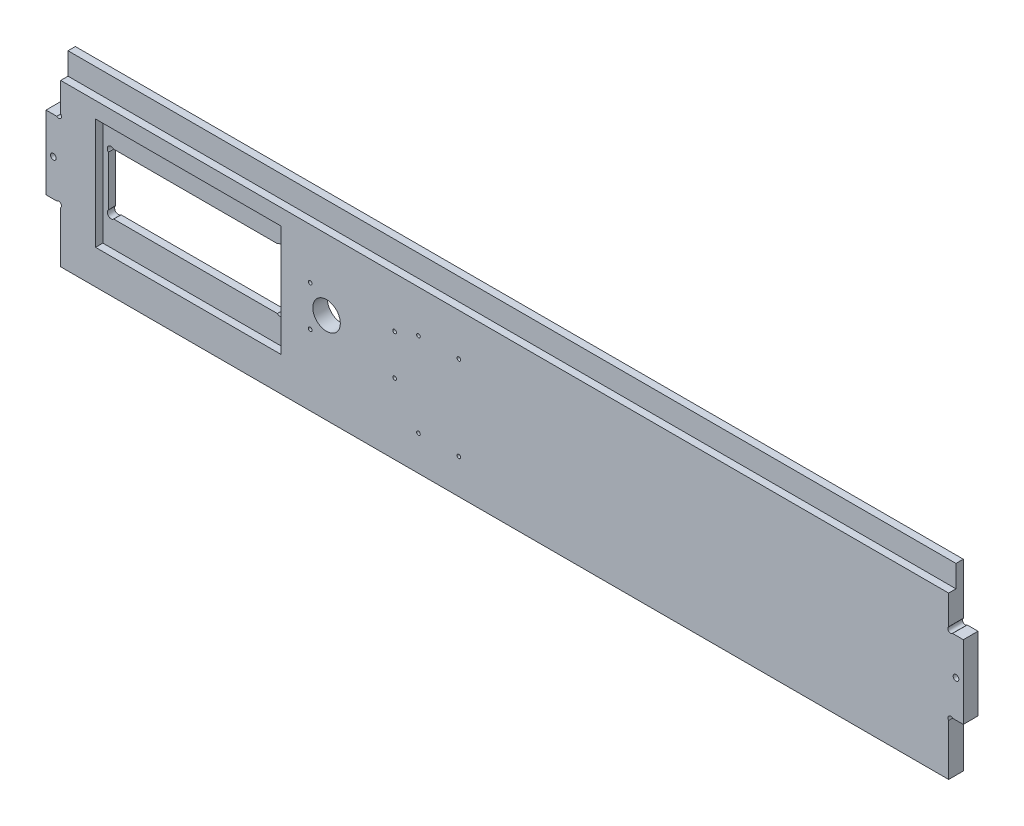
SolidWorks part; units mm, degrees
ref_plane "Plan de face" through (0, 0, 0) normal (0, 0, 1) x (1, 0, 0)
ref_plane "Plan de dessus" through (0, 0, 0) normal (0, 1, 0) x (1, 0, 0)
ref_plane "Plan de droite" through (0, 0, 0) normal (1, 0, 0) x (0, 0, -1)
sketch "Esquisse1" plane through (0, 0, 0) normal (0, 0, 1) x (1, 0, 0)
  line L0 (-399.3886, 52.3509) -> (-399.3886, 24.4722)
  line L1 (-399.3886, 52.3509) -> (84.6114, 52.3509)
  line L2 (-407.3886, 22.3509) -> (-407.3886, -17.6491)
  line L3 (-399.3886, -47.6491) -> (84.6114, -47.6491)
  line L4 (-407.3886, 2.3509) -> (92.6114, 2.3509) construction
  line L5 (-399.3886, -47.6491) -> (-399.3886, -19.7705)
  line L6 (-401.5099, -17.6491) -> (-407.3886, -17.6491)
  line L7 (-401.5099, 22.3509) -> (-407.3886, 22.3509)
  line L8 (-157.3886, 66.6557) -> (-157.3886, -74.1581) construction
  line L9 (84.6114, -47.6491) -> (84.6114, -19.7705)
  line L10 (86.7328, -17.6491) -> (92.6114, -17.6491)
  line L11 (92.6114, 22.3509) -> (92.6114, -17.6491)
  line L12 (86.7328, 22.3509) -> (92.6114, 22.3509)
  line L13 (84.6114, 52.3509) -> (84.6114, 24.4722)
  line L14 (-399.3886, 52.3509) -> (-407.3886, 52.3509) construction
  line L15 (-403.3886, 52.3509) -> (-403.3886, 2.3509) construction
  arc A0 (-401.5099, 22.3509) -> (-399.3886, 24.4722) centre (-400.4492, 23.4115) ccw
  arc A1 (-399.3886, -19.7705) -> (-401.5099, -17.6491) centre (-400.4492, -18.7098) ccw
  arc A2 (84.6114, -19.7705) -> (86.7328, -17.6491) centre (85.6721, -18.7098) cw
  arc A3 (86.7328, 22.3509) -> (84.6114, 24.4722) centre (85.6721, 23.4115) cw
  circle A4 centre (-403.3886, 2.3509) radius 1.55
  circle A5 centre (88.6114, 2.3509) radius 1.55
  dimension "D2" = 1.5
  dimension "D3" = 1.5
  dimension "D4" = 1.5
  dimension "D5" = 1.5
  dimension "D1" = 8
  dimension "D6" = 40
  dimension "D7" = 40
  dimension "D8" = 100
extrude "Boss.-Extru.1" add sketch "Esquisse1" along normal blind 8
sketch "Esquisse2" plane through (0, 0, 8) normal (0, 0, 1) x (1, 0, 0)
  line L0 (84.6114, 52.3509) -> (-399.3886, 52.3509) construction
  line L1 (-414.3283, 52.3509) -> (94.3558, 52.3509)
  line L2 (-414.3283, 52.3509) -> (-414.3283, 40.3509)
  line L3 (-414.3283, 40.3509) -> (94.3558, 40.3509)
  line L4 (94.3558, 52.3509) -> (94.3558, 40.3509)
extrude "Enlèv. mat.-Extru.1" cut sketch "Esquisse2" against normal blind 4
sketch "Esquisse3" plane through (0, 0, 8) normal (0, 0, 1) x (1, 0, 0)
  line L0 (-377.3886, 52.3509) -> (-377.3886, -47.6491) construction
  line L3 (-387.9719, 1.8509) -> (-243.8354, 1.8509) construction
  line L4 (84.6114, 52.3509) -> (-399.3886, 52.3509) construction
  line L5 (-399.3886, -47.6491) -> (84.6114, -47.6491) construction
  line L6 (-377.3886, -14.6491) -> (-362.664, 0.0755) construction
  line L7 (-377.3886, -47.6491) -> (-377.3886, 58.7427) construction
  line L9 (-399.3886, 40.3509) -> (-399.3886, 24.4722) construction
  line L10 (-374.4894, -14.6491) -> (-285.2877, -14.6491)
  line L11 (-377.3886, -11.75) -> (-377.3886, 15.4517)
  line L16 (-329.8886, -29.5481) -> (-329.8886, 25.0007) construction
  line L17 (-387.9719, -14.6491) -> (-275.489, -14.6491) construction
  line L18 (-374.4894, 18.3509) -> (-285.2877, 18.3509)
  line L19 (-282.3886, 15.4517) -> (-282.3886, -11.75)
  line L20 (-254.4762, -23.3434) -> (-254.4762, 13.1981) construction
  arc A0 (-377.3886, -11.75) -> (-374.4894, -14.6491) centre (-375.939, -13.1996) ccw
  arc A1 (-377.3886, 15.4517) -> (-374.4894, 18.3509) centre (-375.939, 16.9013) cw
  arc A2 (-282.3886, 15.4517) -> (-285.2877, 18.3509) centre (-283.8381, 16.9013) ccw
  arc A3 (-282.3886, -11.75) -> (-285.2877, -14.6491) centre (-283.8381, -13.1996) cw
  circle A4 centre (-254.4762, 1.8509) radius 7.5
  point P6 (-399.3886, 32.4115)
  dimension "D6" = 16.5
  dimension "D7" = 47.5
  dimension "D8" = 45
  dimension "D1" = 22
  dimension "D5" = 33
extrude "Enlèv. mat.-Extru.2" cut sketch "Esquisse3" against normal blind 10
sketch "Esquisse4" plane through (0, 0, 8) normal (0, 0, 1) x (1, 0, 0)
  line L0 (-380.3886, 31.6509) -> (-380.3886, -28.9491)
  line L1 (-279.3886, 31.6509) -> (-380.3886, 31.6509)
  line L3 (-374.4894, -14.6491) -> (-285.2877, -14.6491) construction
  line L4 (-377.3886, 15.4517) -> (-377.3886, -11.75) construction
  line L6 (-380.3886, -28.9491) -> (-279.3886, -28.9491)
  line L7 (-279.3886, -28.9491) -> (-279.3886, 31.6509)
  dimension "D1" = 14.3
  dimension "D2" = 101
  dimension "D3" = 3
  dimension "D4" = 60.6
extrude "Enlèv. mat.-Extru.3" cut sketch "Esquisse4" against normal blind 4
sketch "Esquisse5" plane through (0, 0, 8) normal (0, 0, 1) x (1, 0, 0)
  line L0 (-263.3886, -20.9562) -> (-263.3886, 19.9021) construction
  line L1 (-239.6875, 1.8509) -> (-271.0582, 1.8509) construction
  line L2 (-240.3886, -20.9562) -> (-240.3886, 19.9021) construction
  line L3 (-279.3886, -28.9491) -> (-279.3886, 31.6509) construction
  line L4 (-271.0582, -9.1491) -> (-261.5705, -9.1491) construction
  circle A0 centre (-263.3886, -9.1491) radius 1
  circle A1 centre (-263.3886, 12.8509) radius 1
  circle A2 centre (-217.3886, 12.8509) radius 1
  circle A3 centre (-217.3886, -9.1491) radius 1
  circle A4 centre (-204.388, 17.3508) radius 1
  circle A5 centre (-182.3891, 17.3508) radius 1
  circle A6 centre (-204.388, -28.6486) radius 1
  circle A7 centre (-182.3891, -28.6486) radius 1
  dimension "D1" = 16
  dimension "D2" = 23
  dimension "D3" = 11
extrude "Enlèv. mat.-Extru.4" cut sketch "Esquisse5" against normal blind 4
